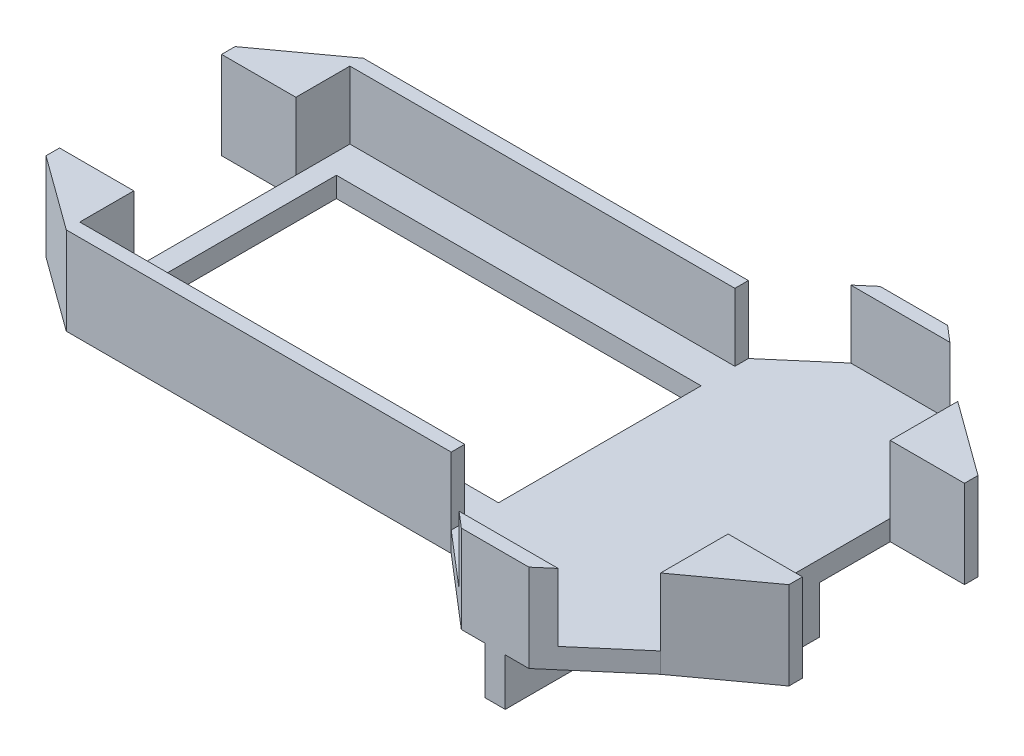
SolidWorks part; units mm, degrees
ref_plane "Front Plane" through (0, 0, 0) normal (0, 0, 1) x (1, 0, 0)
ref_plane "Top Plane" through (0, 0, 0) normal (0, 1, 0) x (1, 0, 0)
ref_plane "Right Plane" through (0, 0, 0) normal (1, 0, 0) x (0, 0, -1)
sketch "Sketch2" plane through (0, 0, 0) normal (0, 1, 0) x (1, 0, 0)
  line L0 (-55, 12) -> (-44, 12)
  line L1 (-55, -14) -> (55, -14) construction
  line L2 (-55, -14) -> (-55, -12)
  line L3 (-55, 14) -> (55, 14) construction
  line L4 (55, -14) -> (55, -12)
  line L5 (-55, -14) -> (55, 14) construction
  line L6 (-55, 14) -> (55, -14) construction
  line L7 (-44, 12) -> (-44, -12)
  line L8 (-44, -12) -> (-55, -12)
  line L9 (-85.0519, 0) -> (93.1845, 0) construction
  line L10 (0, 52.85) -> (0, -45.1883) construction
  line L11 (44, -12) -> (55, -12)
  line L12 (55, 12) -> (44, 12)
  line L13 (44, 12) -> (44, -12)
  line L14 (-55, 12) -> (-55, 14)
  line L15 (-55, 0) -> (-55, 12) construction
  line L16 (-55, -12) -> (-55, 0) construction
  line L17 (55, 12) -> (55, 14)
  line L18 (55, -12) -> (55, 0) construction
  line L19 (55, 0) -> (55, 12) construction
  line L20 (-41, 15) -> (-41, -15)
  line L21 (-41, -15) -> (13, -15)
  line L22 (13, -15) -> (13, 15)
  line L23 (13, 15) -> (-41, 15)
  line L24 (44, 22) -> (-44, 22)
  line L25 (44, -22) -> (-44, -22)
  line L26 (-44, -22) -> (-55, -14)
  line L27 (-44, 22) -> (-55, 14)
  line L28 (44, 22) -> (55, 14)
  line L29 (55, -14) -> (44, -22)
  line L30 (44, 34.0886) -> (44, -41.5625) construction
  point P0 (0, 0)
  point P28 (44, -22)
  point P31 (44, 22)
  point P32 (93.1845, 0)
  dimension "D1" = 28
  dimension "D2" = 110
  dimension "D3" = 12
  dimension "D4" = 88
  dimension "D5" = 3
  dimension "D6" = 30
  dimension "D7" = 7
  dimension "D8" = 54
extrude "Boss-Extrude1" add sketch "Sketch2" along normal blind 3
sketch "Sketch3" plane through (0, 3, 0) normal (0, 1, 0) x (1, 0, 0)
  line L0 (13, 20) -> (-44, 20)
  line L2 (42, -14) -> (42, 14) construction
  line L3 (-44, 12) -> (-44, -12) construction
  line L4 (-51.5996, -14) -> (-43.3496, -20) construction
  line L5 (-43.3496, 20) -> (-51.5996, 14) construction
  line L6 (-44, -12) -> (-44, -20)
  line L8 (-44, -20) -> (13, -20)
  line L9 (-43.3496, -20) -> (43.3496, -20) construction
  line L10 (44, -12) -> (44, 12) construction
  line L11 (44, 12) -> (44, 22)
  line L13 (13, 20) -> (13, 22)
  line L14 (13, -20) -> (13, -22)
  line L15 (43.3496, 20) -> (-43.3496, 20) construction
  line L16 (55, 14) -> (44, 22)
  line L17 (44, 22) -> (-44, 22)
  line L18 (-44, 22) -> (-55, 14)
  line L19 (-55, 14) -> (-55, 12)
  line L20 (-55, 12) -> (-44, 12)
  line L21 (-44, 12) -> (-44, -12)
  line L22 (-44, -12) -> (-55, -12)
  line L23 (-55, -12) -> (-55, -14)
  line L24 (-55, -14) -> (-44, -22)
  line L25 (-44, -22) -> (44, -22)
  line L26 (44, -22) -> (55, -14)
  line L27 (55, -14) -> (55, -12)
  line L28 (55, -12) -> (44, -12)
  line L29 (44, -12) -> (44, 12)
  line L30 (44, 12) -> (55, 12)
  line L31 (55, 12) -> (55, 14)
  line L32 (55, 14) -> (44, 22)
  line L33 (13, 22) -> (-44, 22)
  line L34 (-44, 22) -> (-55, 14)
  line L35 (-55, 14) -> (-55, 12)
  line L36 (-55, 12) -> (-44, 12)
  line L37 (-44, 20) -> (-44, 12)
  line L38 (-44, -12) -> (-55, -12)
  line L39 (-55, -12) -> (-55, -14)
  line L40 (-55, -14) -> (-44, -22)
  line L41 (-44, -22) -> (13, -22)
  line L42 (44, -22) -> (55, -14)
  line L43 (55, -14) -> (55, -12)
  line L44 (55, -12) -> (44, -12)
  line L45 (44, -22) -> (44, -12)
  line L46 (44, 12) -> (55, 12)
  line L47 (55, 12) -> (55, 14)
  line L49 (44, 22) -> (-44, 22) construction
  line L50 (-51.5996, 14) -> (-42, 14) construction
  line L51 (-42, 14) -> (-42, -14) construction
  line L52 (-42, -14) -> (-51.5996, -14) construction
  line L53 (-51.5996, 14) -> (-51.5996, 14) construction
  line L54 (-51.5996, -14) -> (-51.5996, -14) construction
  line L55 (51.5996, 14) -> (43.3496, 20) construction
  line L56 (42, 14) -> (51.5996, 14) construction
  line L57 (51.5996, 14) -> (51.5996, 14) construction
  line L58 (43.3496, -20) -> (51.5996, -14) construction
  line L59 (51.5996, -14) -> (42, -14) construction
  line L60 (51.5996, -14) -> (51.5996, -14) construction
  line L61 (-44, -22) -> (44, -22) construction
  dimension "D3" = 31
  dimension "D1" = 0
  dimension "D2" = 2
extrude "Boss-Extrude2" add sketch "Sketch3" along normal blind 10
sketch "Sketch5" plane through (0, 3, 0) normal (0, 1, 0) x (1, 0, 0)
  line L0 (13, -22) -> (44, -22) construction
  line L1 (44, 22) -> (13, 22) construction
  line L2 (13, -22) -> (44, -22)
  line L3 (44, 22) -> (13, 22)
  line L4 (44, 22) -> (33.5, 31)
  line L5 (33.5, 31) -> (23.5, 31)
  line L6 (23.5, 31) -> (13, 22)
  line L7 (13, -22) -> (23.5, -31)
  line L8 (23.5, -31) -> (33.5, -31)
  line L9 (33.5, -31) -> (44, -22)
  dimension "D1" = 62
  dimension "D2" = 10
extrude "Boss-Extrude4" add sketch "Sketch5" against normal up to surface (3 mm away) up to face at (0, 0, 0)
sketch "Sketch6" plane through (0, 3, 0) normal (0, 1, 0) x (1, 0, 0)
  line L0 (13, -22) -> (23.5, -31) construction
  line L1 (23.5, -31) -> (33.5, -31) construction
  line L2 (33.5, -31) -> (44, -22) construction
  line L3 (44, 22) -> (33.5, 31) construction
  line L4 (33.5, 31) -> (23.5, 31) construction
  line L5 (23.5, 31) -> (13, 22) construction
  line L6 (21.1667, -29) -> (23.5, -31)
  line L7 (23.5, -31) -> (33.5, -31)
  line L8 (33.5, -31) -> (35.8333, -29)
  line L9 (35.8333, 29) -> (33.5, 31)
  line L10 (33.5, 31) -> (23.5, 31)
  line L11 (23.5, 31) -> (21.1667, 29)
  line L12 (35.8333, 29) -> (21.1667, 29)
  line L13 (21.1667, -29) -> (35.8333, -29)
  dimension "D1" = 2
  dimension "D2" = 2
extrude "Boss-Extrude5" add sketch "Sketch6" along normal up to surface (10 mm away) up to face at (-30.8571, 13, 17.4286)
sketch "Sketch4" plane through (0, 0, 0) normal (0, -1, 0) x (1, 0, 0)
  line L0 (-66.828, 0) -> (-35.828, 0) construction
  line L1 (28.5, 31) -> (28.5, -31) construction
  line L2 (13, 15) -> (13, -15) construction
  line L3 (44, 12) -> (44, -12) construction
  line L4 (13, 1.5) -> (13, -1.5)
  line L5 (44, 1.5) -> (44, -1.5)
  line L6 (13, 1.5) -> (27, 1.5)
  line L7 (13, -1.5) -> (27, -1.5)
  line L8 (23.5, 31) -> (33.5, 31) construction
  line L9 (33.5, -31) -> (23.5, -31) construction
  line L10 (23.5, 31) -> (33.5, 31) construction
  line L11 (33.5, -31) -> (23.5, -31) construction
  line L12 (30, 31) -> (30, 1.5)
  line L13 (27, -31) -> (27, -1.5)
  line L14 (30, -1.5) -> (30, -31)
  line L15 (30, 1.5) -> (30, -1.5) construction
  line L16 (27, 1.5) -> (27, 31)
  line L17 (27, -1.5) -> (27, 1.5) construction
  line L18 (30, 1.5) -> (44, 1.5)
  line L19 (28.5, 1.5) -> (30, 1.5) construction
  line L20 (27, 1.5) -> (28.5, 1.5) construction
  line L21 (30, -1.5) -> (44, -1.5)
  line L22 (27, -1.5) -> (28.5, -1.5) construction
  line L23 (28.5, -1.5) -> (30, -1.5) construction
  line L24 (27, -31) -> (30, -31)
  line L25 (27, 31) -> (30, 31)
  dimension "D1" = 3
  dimension "D2" = 3
extrude "Boss-Extrude3" add sketch "Sketch4" along normal blind 7
